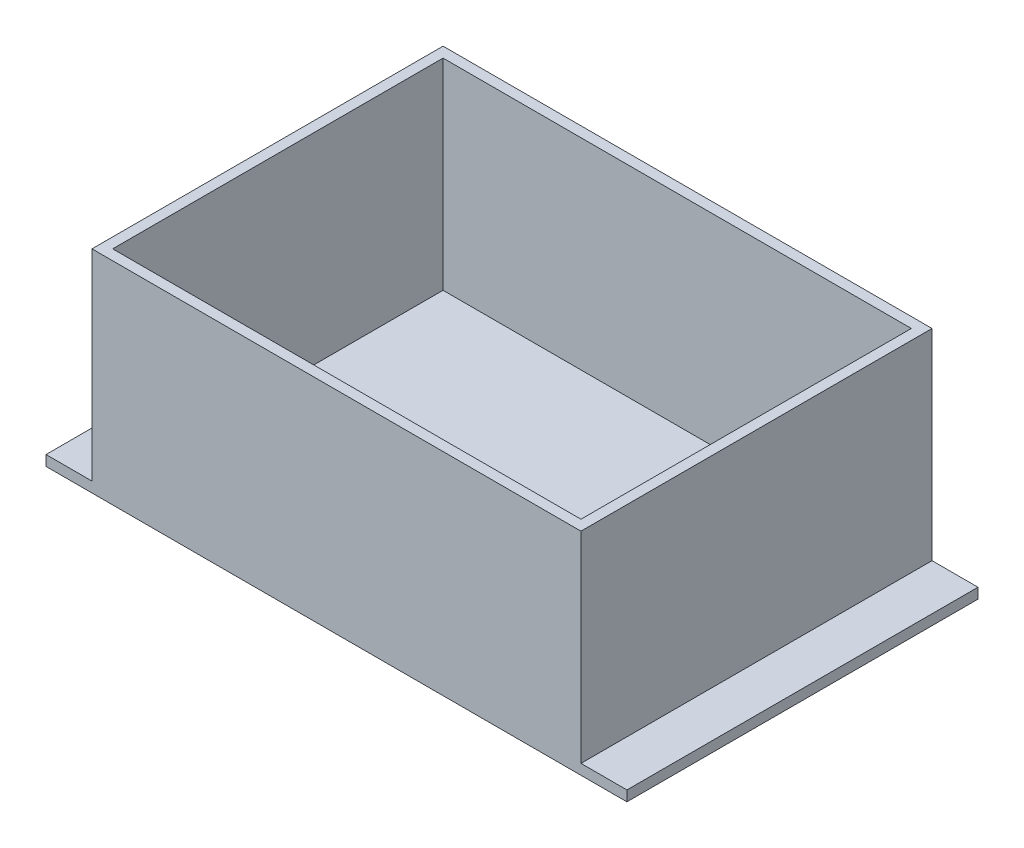
SolidWorks part; units mm, degrees
ref_plane "Front Plane" through (0, 0, 0) normal (0, 0, 1) x (1, 0, 0)
ref_plane "Top Plane" through (0, 0, 0) normal (0, 1, 0) x (1, 0, 0)
ref_plane "Right Plane" through (0, 0, 0) normal (1, 0, 0) x (0, 0, -1)
sketch "Skica1" plane through (0, 0, 0) normal (0, 1, 0) x (1, 0, 0)
  line L0 (-1.8, 59.3) -> (83.3, 59.3)
  line L1 (0, 0) -> (81.5, 0)
  line L2 (0, 0) -> (0, 57.5)
  line L3 (0, 57.5) -> (81.5, 57.5)
  line L4 (81.5, 0) -> (81.5, 57.5)
  line L5 (83.3, -1.8) -> (83.3, 59.3)
  line L6 (-1.8, -1.8) -> (83.3, -1.8)
  line L7 (-1.8, -1.8) -> (-1.8, 59.3)
  dimension "D1" = 81.5
  dimension "D2" = 57.5
  dimension "D3" = 1.8
extrude "Přidat vysunutím1" add sketch "Skica1" along normal blind 35
sketch "Skica2" plane through (0, 0, 0) normal (0, -1, 0) x (1, 0, 0)
  line L0 (-1.8, -59.3) -> (-1.8, 1.8) construction
  line L1 (-9.8, 1.8) -> (91.3, 1.8)
  line L2 (-9.8, 1.8) -> (-9.8, -59.3)
  line L3 (-9.8, -59.3) -> (91.3, -59.3)
  line L4 (91.3, 1.8) -> (91.3, -59.3)
  line L5 (83.3, 1.8) -> (83.3, -59.3) construction
  dimension "D1" = 8
  dimension "D2" = 8
extrude "Přidat vysunutím2" add sketch "Skica2" along normal blind 1.8
sketch "Skica3" plane through (0, 0, 0) normal (0, 1, 0) x (1, 0, 0)
  line L1 (0, 57.5) -> (0, 0) construction
  circle A0 centre (15.44, 54.1049) radius 1.7
  circle A1 centre (14.14, 5.9049) radius 1.7
  circle A2 centre (66.24, 38.9049) radius 1.7
  circle A3 centre (66.24, 11.0049) radius 1.7
  dimension "D1" = 27.9
  dimension "D2" = 15.2
  dimension "D3" = 66.24
  dimension "D4" = 50.8
  dimension "D5" = 1.3
  dimension "D6" = 5.1
